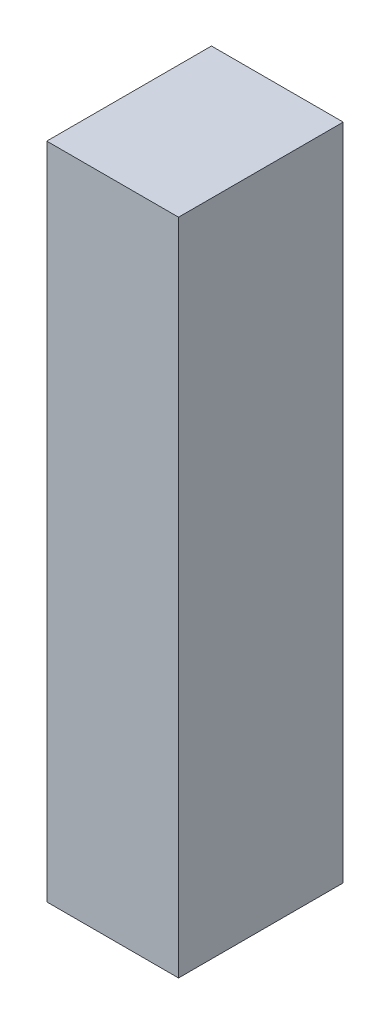
SolidWorks part; units mm, degrees
ref_plane "Front Plane" through (0, 0, 0) normal (0, 0, 1) x (1, 0, 0)
ref_plane "Top Plane" through (0, 0, 0) normal (0, 1, 0) x (1, 0, 0)
ref_plane "Right Plane" through (0, 0, 0) normal (1, 0, 0) x (0, 0, -1)
sketch "Sketch1" plane through (0, 0, 0) normal (0, 1, 0) x (1, 0, 0)
  line L1 (-6, 7.5) -> (6, 7.5)
  line L2 (-6, 7.5) -> (-6, -7.5)
  line L3 (-6, -7.5) -> (6, -7.5)
  line L4 (6, 7.5) -> (6, -7.5)
  line L5 (-6, 7.5) -> (6, -7.5) construction
  line L6 (-6, -7.5) -> (6, 7.5) construction
  point P0 (0, 0)
  dimension "D1" = 12
  dimension "D2" = 15
extrude "Boss-Extrude1" add sketch "Sketch1" along normal blind 10 and the other way blind 50
scale "25% Scale" bodies to scale 101 scale about centroid uniform scaling yes scale factor 0.25
